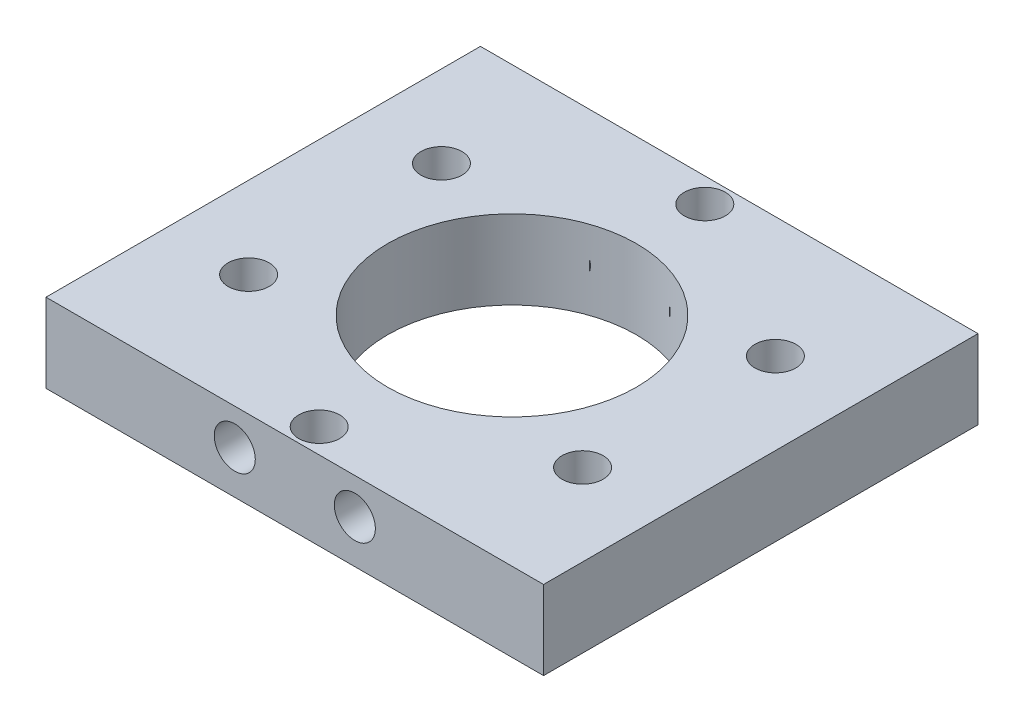
SolidWorks part; units mm, degrees
ref_plane "Front Plane" through (0, 0, 0) normal (0, 0, 1) x (1, 0, 0)
ref_plane "Top Plane" through (0, 0, 0) normal (0, 1, 0) x (1, 0, 0)
ref_plane "Right Plane" through (0, 0, 0) normal (1, 0, 0) x (0, 0, -1)
sketch "Sketch1" plane through (0, 0, 0) normal (0, 0, 1) x (1, 0, 0)
  line L1 (0, 0) -> (40, 0)
  line L2 (0, 0) -> (0, 6.35)
  line L3 (0, 6.35) -> (40, 6.35)
  line L4 (40, 0) -> (40, 6.35)
  dimension "D1" = 40
  dimension "D2" = 6.35
extrude "Boss-Extrude1" add sketch "Sketch1" along normal blind 34.925
sketch "Sketch2" plane through (0, 0, 34.925) normal (0, 0, 1) x (1, 0, 0)
  line L0 (0, 6.35) -> (0, 0) construction
  line L1 (40, 6.35) -> (0, 6.35) construction
  line L2 (15.174, 3.4721) -> (24.826, 3.4721) construction
  circle A0 centre (15.174, 3.4721) radius 1.651
  circle A1 centre (24.826, 3.4721) radius 1.651
  point P4 (20, 3.4721)
  point P5 (0, 3.175)
  point P6 (20, 6.35)
  dimension "D1" = 3.302
  dimension "D2" = 9.652
extrude "Cut-Extrude1" cut sketch "Sketch2" against normal blind 8
ref_plane "Plane1" through (0, 0, 17.4625) normal (0, 0, 1) x (1, 0, 0)
mirror "Mirror1" about plane through (0, 0, 17.4625) normal (0, 0, 1) of "Cut-Extrude1"
sketch "Sketch3" plane through (0, 6.35, 0) normal (0, 1, 0) x (1, 0, 0)
  line L0 (40, 0) -> (0, 0) construction
  line L1 (0, -34.925) -> (0, 0) construction
  circle A0 centre (20, -17.4625) radius 10
  point P2 (20, 0)
  point P3 (0, -17.4625)
  dimension "D1" = 20
extrude "Cut-Extrude2" cut sketch "Sketch3" against normal through all
sketch "Sketch4" plane through (0, 6.35, 0) normal (0, 1, 0) x (1, 0, 0)
  circle A0 centre (20, -1.9625) radius 1.65
  circle A1 centre (20, -17.4625) radius 10 construction
  point P5 (20, -17.4625)
  dimension "D2" = 3.3
  dimension "D1" = 15.5
extrude "Cut-Extrude3" cut sketch "Sketch4" against normal through all
pattern_circular "CirPattern1" count 6 over 360 about axis through (20, 0, 17.4625) along (0, 1, 0) of "Cut-Extrude3"
ref_plane "Plane2" through (0, 0, 17.4625) normal (0, 0, 1) x (1, 0, 0)
